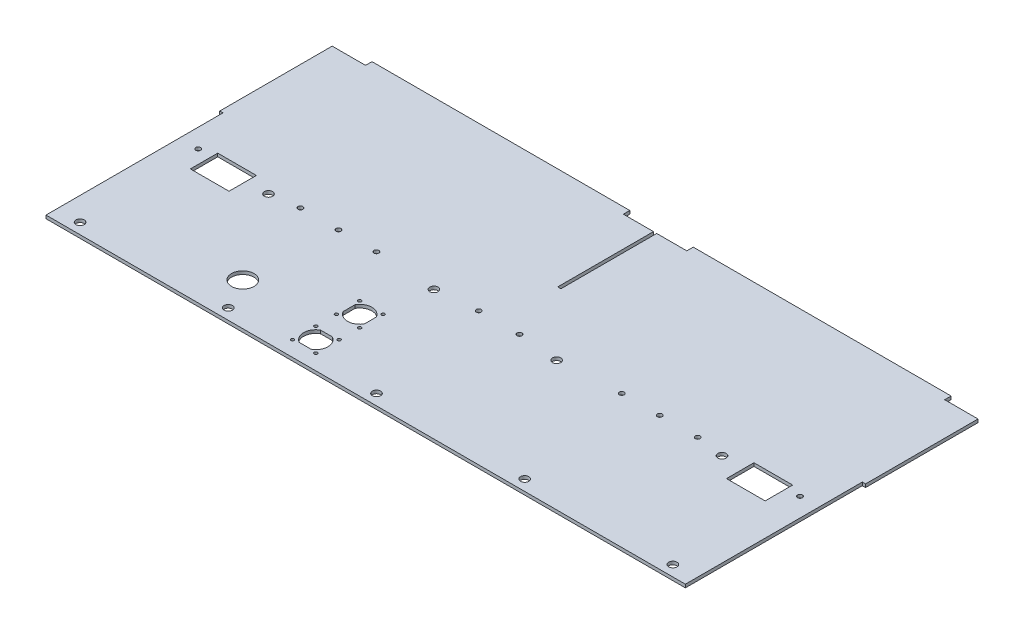
SolidWorks part; units mm, degrees
material "6061-T6 (SS)"
ref_plane "X-Y Datum" through (0, 0, 0) normal (0, 0, 1) x (1, 0, 0)
ref_plane "X-Z Datum" through (0, 0, 0) normal (0, 1, 0) x (1, 0, 0)
ref_plane "Y-Z Datum" through (0, 0, 0) normal (1, 0, 0) x (0, 0, -1)
sketch "Sketch1" plane through (0, 0, 0) normal (0, 1, 0) x (1, 0, 0)
  line L1 (0, 0) -> (629.9098, 0)
  line L2 (0, 0) -> (0, 147.6985)
  line L3 (0, 147.6985) -> (629.9098, 147.6985)
  line L4 (629.9098, 0) -> (629.9098, 147.6985)
extrude "Boss-Extrude1" add sketch "Sketch1" along normal blind 3.175
sketch "Sketch3" plane through (0, 0, -147.6985) normal (0, 0, -1) x (-1, 0, 0)
  line L0 (-629.9098, 0) -> (0, 0) construction
  line L1 (-629.9098, 0) -> (-629.9098, 3.175) construction
  line L2 (-629.9098, 3.175) -> (0, 3.175) construction
  line L3 (0, 0) -> (0, 3.175) construction
  line L4 (-600.2261, 0) -> (-346.2261, 0)
  line L5 (-600.2261, 0) -> (-600.2261, 3.175)
  line L6 (-600.2261, 3.175) -> (-346.2261, 3.175)
  line L7 (-346.2261, 0) -> (-346.2261, 3.175)
  line L8 (-283.6837, 0) -> (-29.6837, 0)
  line L9 (-283.6837, 0) -> (-283.6837, 3.175)
  line L10 (-283.6837, 3.175) -> (-29.6837, 3.175)
  line L11 (-29.6837, 0) -> (-29.6837, 3.175)
extrude "Boss-Extrude2" add sketch "Sketch3" along normal blind 6.35
sketch "Sketch4" plane through (0, 3.175, 0) normal (0, 1, 0) x (1, 0, 0)
  line L0 (346.2261, 147.6985) -> (283.6837, 147.6985) construction
  line L1 (313.3674, 53.332) -> (316.5424, 53.332)
  line L2 (313.3674, 53.332) -> (313.3674, 242.0649)
  line L3 (313.3674, 242.0649) -> (316.5424, 242.0649)
  line L4 (316.5424, 53.332) -> (316.5424, 242.0649)
  line L5 (313.3674, 53.332) -> (316.5424, 242.0649) construction
  line L6 (313.3674, 242.0649) -> (316.5424, 53.332) construction
  point P0 (314.9549, 147.6985)
extrude "Cut-Extrude1" cut sketch "Sketch4" against normal blind 3.175
sketch "Sketch6" plane through (0, 3.175, 0) normal (0, 1, 0) x (1, 0, 0)
  line L0 (314.9549, 53.332) -> (314.9549, 202.815) construction
  line L6 (629.9098, 36.9246) -> (633.0848, 36.9246)
  line L7 (633.0848, 147.6985) -> (633.0848, 36.9246)
  line L8 (629.9098, 147.6985) -> (633.0848, 147.6985)
  line L9 (629.9098, 147.6985) -> (629.9098, 36.9246)
  line L10 (0, 147.6985) -> (0, 36.9246)
  line L11 (0, 147.6985) -> (-3.175, 147.6985)
  line L12 (-3.175, 147.6985) -> (-3.175, 36.9246)
  line L13 (0, 36.9246) -> (-3.175, 36.9246)
extrude "Boss-Extrude4" add sketch "Sketch6" against normal blind 3.175
sketch "Sketch8" plane through (0, 3.175, 0) normal (0, 1, 0) x (1, 0, 0)
  line L1 (0, 0) -> (629.9098, 0)
  line L2 (0, 0) -> (0, -18.0442)
  line L3 (0, -18.0442) -> (629.9098, -18.0442)
  line L4 (629.9098, 0) -> (629.9098, -18.0442)
extrude "Boss-Extrude5" add sketch "Sketch8" against normal through all
sketch "Sketch9" plane through (0, 3.175, 0) normal (0, 1, 0) x (1, 0, 0)
  line L0 (0, -18.0442) -> (47.8104, -18.0442) construction
  line L1 (0, -18.0442) -> (629.9098, -18.0442) construction
  line L2 (314.9549, -18.0442) -> (314.9549, 180.2876) construction
  line L3 (30.0304, -36.0782) -> (65.5904, -36.0782)
  line L4 (30.0304, -36.0782) -> (30.0304, -0.0102)
  line L5 (30.0304, -0.0102) -> (65.5904, -0.0102)
  line L6 (65.5904, -36.0782) -> (65.5904, -0.0102)
  line L7 (30.0304, -36.0782) -> (65.5904, -0.0102) construction
  line L8 (30.0304, -0.0102) -> (65.5904, -36.0782) construction
  line L9 (599.8794, -0.0102) -> (564.3194, -0.0102)
  line L10 (564.3194, -36.0782) -> (564.3194, -0.0102)
  line L11 (599.8794, -36.0782) -> (564.3194, -36.0782)
  line L12 (599.8794, -36.0782) -> (599.8794, -0.0102)
extrude "Cut-Extrude2" [suppressed] cut sketch "Sketch9" against normal through all
sketch "Sketch10" plane through (0, 3.175, 0) normal (0, 1, 0) x (1, 0, 0)
  line L0 (313.3674, 53.332) -> (313.3674, -18.0442) construction
  line L1 (314.9549, -18.0442) -> (314.9549, -25.2417) construction
  line L2 (0, -18.0442) -> (629.9098, -18.0442) construction
  line L3 (313.3674, -18.0442) -> (281.6174, -18.0442) construction
  line L4 (348.2924, 0) -> (386.3924, 0) construction
  line L5 (281.6174, -18.0442) -> (243.5174, -18.0442) construction
  line L6 (281.6174, -18.0442) -> (281.6174, 0) construction
  line L7 (281.6174, 0) -> (243.5174, 0) construction
  line L8 (243.5174, -18.0442) -> (243.5174, 0) construction
  line L9 (386.3924, -18.0442) -> (386.3924, 0) construction
  line L10 (348.2924, -18.0442) -> (386.3924, -18.0442) construction
  line L11 (348.2924, -18.0442) -> (348.2924, 0) construction
  line L12 (0, -18.0442) -> (50.8, -18.0442) construction
  line L13 (0, -18.0442) -> (629.9098, -18.0442) construction
  line L22 (598.1598, 0) -> (560.0598, 0)
  line L23 (31.75, -36.0883) -> (69.85, -36.0883)
  line L24 (31.75, -36.0883) -> (31.75, 0)
  line L25 (31.75, 0) -> (69.85, 0)
  line L26 (69.85, -36.0883) -> (69.85, 0)
  line L27 (31.75, -36.0883) -> (69.85, 0) construction
  line L28 (31.75, 0) -> (69.85, -36.0883) construction
  line L29 (560.0598, -36.0883) -> (560.0598, 0)
  line L30 (598.1598, -36.0883) -> (560.0598, -36.0883)
  line L31 (598.1598, -36.0883) -> (598.1598, 0)
  line L32 (0, 36.9246) -> (0, -18.0442) construction
  dimension "D1" = 31.75
  dimension "D2" = 38.1
  dimension "D3" = 50.8
extrude "Cut-Extrude3" cut sketch "Sketch10" against normal through all
sketch "Sketch11" plane through (0, 3.175, 0) normal (0, 1, 0) x (1, 0, 0)
  line L2 (0, -18.0442) -> (0, -137.4242)
  line L3 (0, -137.4242) -> (629.9098, -137.4242)
  line L4 (629.9098, -18.0442) -> (629.9098, -137.4242)
  line L5 (314.9549, -18.0442) -> (629.9098, -137.4242) construction
  line L6 (0, -137.4242) -> (314.9549, -18.0442) construction
  line L7 (0, -18.0442) -> (31.75, -18.0442)
  line L8 (281.6174, -18.0442) -> (348.2924, -18.0442)
  line L10 (243.5174, -18.0442) -> (243.5174, -26.9519) construction
  line L11 (243.5174, -26.9519) -> (281.6174, -26.9519) construction
  line L12 (281.6174, -18.0442) -> (281.6174, -26.9519) construction
  line L14 (348.2924, -18.0442) -> (348.2924, -27.0662) construction
  line L15 (348.2924, -27.0662) -> (386.3924, -27.0662) construction
  line L16 (386.3924, -18.0442) -> (386.3924, -27.0662) construction
  line L17 (386.3924, -18.0442) -> (560.0598, -18.0442)
  line L18 (31.75, -18.0442) -> (31.75, -26.9519)
  line L19 (31.75, -26.9519) -> (69.85, -26.9519)
  line L20 (69.85, -26.9519) -> (69.85, -18.0442)
  line L21 (560.0598, -18.0442) -> (560.0598, -27.0662)
  line L22 (560.0598, -27.0662) -> (598.1598, -27.0662)
  line L23 (598.1598, -27.0662) -> (598.1598, -18.0442)
  line L24 (69.85, -18.0442) -> (243.5174, -18.0442)
  line L25 (598.1598, -18.0442) -> (629.9098, -18.0442)
  line L26 (243.5174, -18.0442) -> (281.6174, -18.0442)
  line L27 (348.2924, -18.0442) -> (386.3924, -18.0442)
  point P0 (314.9549, -18.0442)
extrude "Boss-Extrude6" add sketch "Sketch11" against normal through all
sketch "Sketch12" [suppressed] plane through (0, 3.175, 0) normal (0, 1, 0) x (1, 0, 0)
  line L1 (31.75, 0) -> (69.85, 0)
  line L2 (31.75, 0) -> (31.75, -18.0442)
  line L3 (31.75, -18.0442) -> (69.85, -18.0442)
  line L4 (69.85, 0) -> (69.85, -18.0442)
  line L5 (560.0598, 0) -> (598.1598, 0)
  line L6 (560.0598, 0) -> (560.0598, -18.0442)
  line L7 (560.0598, -18.0442) -> (598.1598, -18.0442)
  line L8 (598.1598, 0) -> (598.1598, -18.0442)
extrude "Boss-Extrude7" [suppressed] add sketch "Sketch12" against normal through all
sketch "Sketch13" plane through (0, 0, 0) normal (0, -1, 0) x (1, 0, 0)
  line L0 (244.9105, 120.8318) -> (233.5527, 120.8318) construction
  line L1 (244.9105, 100.8318) -> (233.5527, 100.8318) construction
  line L2 (249.2316, 73.2621) -> (249.2316, 61.9043) construction
  line L3 (229.2316, 73.2621) -> (229.2316, 61.9043) construction
  line L4 (245.0431, 100.3238) -> (233.42, 100.3238)
  line L5 (245.0431, 121.3398) -> (233.42, 121.3398)
  line L6 (249.7396, 73.3947) -> (249.7396, 61.7716)
  line L7 (228.7236, 73.3947) -> (228.7236, 61.7716)
  line L8 (2.2083, 136.32) -> (632.1181, 136.32) construction
  line L9 (2.2083, 136.32) -> (2.2083, 49.1456) construction
  line L10 (2.2083, 49.1456) -> (632.1181, 49.1456) construction
  line L11 (632.1181, 136.32) -> (632.1181, 49.1456) construction
  circle A0 centre (227.7316, 122.3318) radius 1.55
  circle A1 centre (250.7316, 122.3318) radius 1.55
  circle A2 centre (227.7316, 99.3318) radius 1.55
  circle A3 centre (250.7316, 99.3318) radius 1.55
  circle A4 centre (152.3285, 95.8779) radius 11.049
  circle A5 centre (227.7316, 79.0832) radius 1.55
  circle A6 centre (227.7316, 56.0832) radius 1.55
  circle A7 centre (250.7316, 56.0832) radius 1.55
  circle A8 centre (250.7316, 79.0832) radius 1.55
  arc A9 (249.2316, 73.2621) -> (229.2316, 73.2621) centre (239.2316, 67.5832) ccw construction
  arc A10 (249.2316, 61.9043) -> (229.2316, 61.9043) centre (239.2316, 67.5832) cw construction
  arc A11 (244.9105, 120.8318) -> (244.9105, 100.8318) centre (239.2316, 110.8318) cw construction
  arc A12 (233.5527, 120.8318) -> (233.5527, 100.8318) centre (239.2316, 110.8318) ccw construction
  arc A13 (233.42, 121.3398) -> (233.42, 100.3238) centre (239.2316, 110.8318) ccw
  arc A14 (245.0431, 121.3398) -> (245.0431, 100.3238) centre (239.2316, 110.8318) cw
  arc A15 (249.7396, 61.7716) -> (228.7236, 61.7716) centre (239.2316, 67.5832) cw
  arc A16 (249.7396, 73.3947) -> (228.7236, 73.3947) centre (239.2316, 67.5832) ccw
extrude "Cut-Extrude4" cut sketch "Sketch13" against normal through all
sketch "Sketch14" plane through (0, 0, 0) normal (0, -1, 0) x (1, 0, 0)
  line L0 (0, 137.4242) -> (653.3937, 137.4242) construction
  line L1 (0, 137.4242) -> (0, -17.9044) construction
  line L2 (0, -17.9044) -> (653.3937, -17.9044) construction
  line L3 (653.3937, 137.4242) -> (653.3937, -17.9044) construction
  point P0 (11.811, 127.2642)
  point P1 (163.383, 127.2642)
  point P2 (314.9549, 127.2642)
  point P3 (466.5269, 127.2642)
  point P4 (618.0988, 127.2642)
  point P5 (618.0988, 38.1102)
  point P6 (466.5269, 38.1102)
  point P7 (314.9549, 38.1102)
  point P8 (163.383, 38.1102)
  point P9 (11.811, 38.1102)
sketch "Sketch17" [suppressed] plane through (0, 3.175, 0) normal (0, 1, 0) x (1, 0, 0)
  line L1 (243.5174, -18.0442) -> (281.6174, -18.0442)
  line L2 (243.5174, -18.0442) -> (243.5174, 0)
  line L3 (243.5174, 0) -> (281.6174, 0)
  line L4 (281.6174, -18.0442) -> (281.6174, 0)
  line L5 (348.2924, -18.0442) -> (386.3924, -18.0442)
  line L6 (348.2924, -18.0442) -> (348.2924, 0)
  line L7 (348.2924, 0) -> (386.3924, 0)
  line L8 (386.3924, -18.0442) -> (386.3924, 0)
extrude "Cut-Extrude5" [suppressed] cut sketch "Sketch17" against normal through all
sketch "Sketch18" [suppressed] plane through (0, 3.175, 0) normal (0, 1, 0) x (1, 0, 0)
  line L0 (0, 36.9246) -> (0, -18.0442) construction
  line L1 (104.9274, 0.4059) -> (143.0274, 0.4059)
  line L2 (104.9274, 0.4059) -> (104.9274, -18.0442)
  line L3 (104.9274, -18.0442) -> (143.0274, -18.0442)
  line L4 (143.0274, 0.4059) -> (143.0274, -18.0442)
  line L10 (314.752, 53.332) -> (314.752, 40.2478) construction
  line L16 (386.3924, -18.0442) -> (629.9098, -18.0442) construction
  line L17 (567.7073, -18.0442) -> (529.6073, -18.0442)
  line L18 (567.7073, -18.0442) -> (567.7073, 0.4059)
  line L19 (567.7073, 0.4059) -> (529.6073, 0.4059)
  line L20 (529.6073, -18.0442) -> (529.6073, 0.4059)
  line L21 (0, -18.0442) -> (243.5174, -18.0442) construction
  line L22 (629.9098, -18.0442) -> (629.9098, 36.9246) construction
  dimension "D1" = 38.1
  dimension "D2" = 104.9274
  dimension "D3" = 38.1
  dimension "D4" = 62.2025
extrude "Cut-Extrude6" [suppressed] cut sketch "Sketch18" against normal through all
sketch "Sketch20" plane through (0, 0, 0) normal (0, -1, 0) x (1, 0, 0)
  line L0 (269.9465, 71.4811) -> (278.9364, 71.4811)
  line L1 (258.3414, 113.1615) -> (278.9364, 113.1615)
  line L2 (258.3414, 113.1615) -> (258.3414, 110.2194)
  line L3 (258.3414, 110.2194) -> (278.9364, 110.2194)
  line L4 (278.9364, 113.1615) -> (278.9364, 110.2194)
  line L5 (258.3414, 71.4811) -> (266.1871, 71.4811)
  line L6 (258.3414, 71.4811) -> (258.3414, 69.3563)
  line L7 (258.3414, 69.3563) -> (266.1871, 69.3563)
  line L8 (278.9364, 71.4811) -> (278.9364, 69.3563)
  line L9 (266.1871, 79) -> (269.9465, 79)
  line L10 (266.1871, 79) -> (266.1871, 71.4811)
  line L11 (266.1871, 61.8375) -> (269.9465, 61.8375)
  line L12 (269.9465, 79) -> (269.9465, 71.4811)
  line L13 (269.9465, 69.3563) -> (269.9465, 61.8375)
  line L14 (269.9465, 69.3563) -> (278.9364, 69.3563)
  line L15 (266.1871, 69.3563) -> (266.1871, 61.8375)
extrude "Cut-Extrude7" cut sketch "Sketch20" against normal blind 1.27
sketch "Sketch21" plane through (0, 3.175, 0) normal (0, 1, 0) x (1, 0, 0)
  line L0 (0, -137.4242) -> (8.6479, -137.4242) construction
  line L1 (0, -137.4242) -> (0, -125.2168) construction
  line L2 (0, -125.2168) -> (8.6479, -125.2168) construction
  line L3 (8.6479, -137.4242) -> (8.6479, -125.2168) construction
  line L4 (314.9549, 53.332) -> (314.9549, 36.3364) construction
  line L5 (313.3674, 53.332) -> (316.5424, 53.332) construction
  circle A1 centre (168.9435, -126.7866) radius 4.064
  circle A2 centre (314.9549, -126.7866) radius 4.064
  circle A3 centre (460.9663, -126.7866) radius 4.064
  circle A4 centre (606.9777, -126.7866) radius 4.064
  circle A5 centre (22.9321, -126.7866) radius 4.064
  point P1 (168.9435, -126.7866)
  point P2 (314.9549, -126.7866)
  point P3 (460.9663, -126.7866)
  point P4 (606.9777, -126.7866)
  point P9 (0, -137.4242)
extrude "Cut-Extrude8" cut sketch "Sketch21" against normal through all
sketch "Sketch22" [suppressed] plane through (0, 3.175, 0) normal (0, 1, 0) x (1, 0, 0)
  line L6 (0, -7.747) -> (104.9274, -7.747) construction
  line L9 (0, 36.9246) -> (0, -18.0442) construction
  line L12 (104.9274, 0.4059) -> (104.9274, -18.0442) construction
  line L15 (143.0274, -7.747) -> (243.5174, -7.747) construction
  line L16 (143.0274, -18.0442) -> (143.0274, 0.4059) construction
  line L17 (243.5174, 0) -> (243.5174, -18.0442) construction
  line L18 (281.6174, -7.747) -> (348.2924, -7.747) construction
  line L19 (281.6174, -18.0442) -> (281.6174, 0) construction
  line L20 (348.2924, 0) -> (348.2924, -18.0442) construction
  line L21 (386.3924, -7.747) -> (529.6073, -7.747) construction
  line L24 (386.3924, -18.0442) -> (386.3924, 0) construction
  line L25 (529.6073, 0.4059) -> (529.6073, -18.0442) construction
  line L26 (567.7073, -7.747) -> (629.9098, -7.747) construction
  line L27 (567.7073, -18.0442) -> (567.7073, 0.4059) construction
  line L28 (629.9098, -18.0442) -> (629.9098, 36.9246) construction
  circle A0 centre (53.9598, -7.747) radius 4.064
  circle A1 centre (193.2724, -7.747) radius 4.064
  circle A2 centre (314.9549, -7.747) radius 4.064
  circle A3 centre (457.9999, -7.747) radius 4.064
  circle A4 centre (597.3125, -7.747) radius 4.064
extrude "Cut-Extrude9" [suppressed] cut sketch "Sketch22" against normal through all
sketch "Sketch23" plane through (0, 3.175, 0) normal (0, 1, 0) x (1, 0, 0)
  line L0 (538.3475, -12.829) -> (538.3475, -6.729) construction
  line L1 (375.4057, -12.829) -> (375.4057, -6.729) construction
  line L2 (254.5042, -12.829) -> (254.5042, -6.729) construction
  line L3 (91.5623, -12.829) -> (91.5623, -6.729) construction
  line L4 (629.9098, -137.4242) -> (403.1779, -137.4242) construction
  line L5 (629.9098, -137.4242) -> (629.9098, -43.8281) construction
  line L6 (629.9098, -43.8281) -> (403.1779, -43.8281) construction
  line L7 (403.1779, -137.4242) -> (403.1779, -43.8281) construction
  circle A0 centre (538.3475, -9.779) radius 4.064
  circle A1 centre (375.4057, -9.779) radius 4.064
  circle A2 centre (254.5042, -9.779) radius 4.064
  circle A3 centre (91.5623, -9.779) radius 4.064
  point P20 (629.9098, -137.4242)
extrude "Cut-Extrude10" cut sketch "Sketch23" against normal through all
sketch "Sketch24" [suppressed] plane through (0, 3.175, 0) normal (0, 1, 0) x (1, 0, 0)
  line L0 (314.9549, -18.0442) -> (314.9549, -44.4855) construction
  line L1 (0, -18.0442) -> (5.08, -18.0442)
  line L2 (0, -18.0442) -> (0, -5.3442)
  line L3 (0, -5.3442) -> (5.08, -5.3442)
  line L4 (5.08, -18.0442) -> (5.08, -5.3442)
  line L6 (629.9098, -5.3442) -> (624.8298, -5.3442)
  line L7 (624.8298, -18.0442) -> (624.8298, -5.3442)
  line L8 (629.9098, -18.0442) -> (624.8298, -18.0442)
  line L9 (629.9098, -18.0442) -> (629.9098, -5.3442)
extrude "Cut-Extrude11" [suppressed] cut sketch "Sketch24" against normal through all
sketch "Sketch25" plane through (0, 3.175, 0) normal (0, 1, 0) x (1, 0, 0)
  line L0 (629.9098, -18.0442) -> (0, -18.0442) construction
  line L1 (629.9098, -18.0442) -> (629.9098, 147.6985) construction
  line L2 (629.9098, 147.6985) -> (0, 147.6985) construction
  line L3 (0, -18.0442) -> (0, 147.6985) construction
  line L4 (613.8026, -5.9968) -> (609.002, -5.9968)
  line L5 (513.0512, -5.9968) -> (508.2506, -5.9968)
  line L6 (475.6264, -5.9968) -> (470.8258, -5.9968)
  line L7 (438.2017, -5.9968) -> (433.4011, -5.9968)
  line L8 (337.45, -5.9968) -> (332.6497, -5.9968)
  line L9 (314.9549, 53.332) -> (314.9549, 20.4386) construction
  line L10 (313.3674, 53.332) -> (316.5424, 53.332) construction
  line L11 (292.4599, -5.9968) -> (297.2602, -5.9968)
  line L12 (191.7082, -5.9968) -> (196.5088, -5.9968)
  line L13 (154.2834, -5.9968) -> (159.084, -5.9968)
  line L14 (116.8586, -5.9968) -> (121.6592, -5.9968)
  line L15 (16.1072, -5.9968) -> (20.9078, -5.9968)
hole_wizard "M4 Clearance Hole1" positions "Sketch28" profile "Sketch29" hole size "M4" standard "ANSI Metric" end condition through all
sketch "Sketch28" plane through (0, 3.175, 0) normal (0, 1, 0) x (1, 0, 0)
  line L0 (613.8026, -5.9968) -> (609.002, -5.9968) construction
  line L1 (513.0512, -5.9968) -> (508.2506, -5.9968) construction
  line L2 (475.6264, -5.9968) -> (470.8258, -5.9968) construction
  line L3 (438.2017, -5.9968) -> (433.4011, -5.9968) construction
  line L4 (337.45, -5.9968) -> (332.6497, -5.9968) construction
  line L5 (292.4599, -5.9968) -> (297.2602, -5.9968) construction
  line L6 (191.7082, -5.9968) -> (196.5088, -5.9968) construction
  line L7 (154.2834, -5.9968) -> (159.084, -5.9968) construction
  line L8 (116.8586, -5.9968) -> (121.6592, -5.9968) construction
  line L9 (16.1072, -5.9968) -> (20.9078, -5.9968) construction
  point P0 (611.4023, -5.9968)
  point P4 (510.6509, -5.9968)
  point P8 (473.2261, -5.9968)
  point P12 (435.8014, -5.9968)
  point P16 (335.0498, -5.9968)
  point P20 (294.86, -5.9968)
  point P24 (194.1085, -5.9968)
  point P28 (156.6837, -5.9968)
  point P32 (119.2589, -5.9968)
  point P36 (18.5075, -5.9968)
sketch "Sketch29" plane through (611.4023, 3.175, 5.9968) normal (1, 0, 0) x (0, 0, 1)
  line L0 (0, 0) -> (0, 3.175)
  line L1 (0, 3.175) -> (2.4, 3.175)
  line L2 (2.4, 3.175) -> (2.4, 0)
  line L5 (2.4, 0) -> (0, 0)
  line L11 (0, -6.35) -> (0, 107.95) construction
  dimension "Thru Hole Dia." = 4.8
  dimension "Thru Hole Depth" = 3.175
